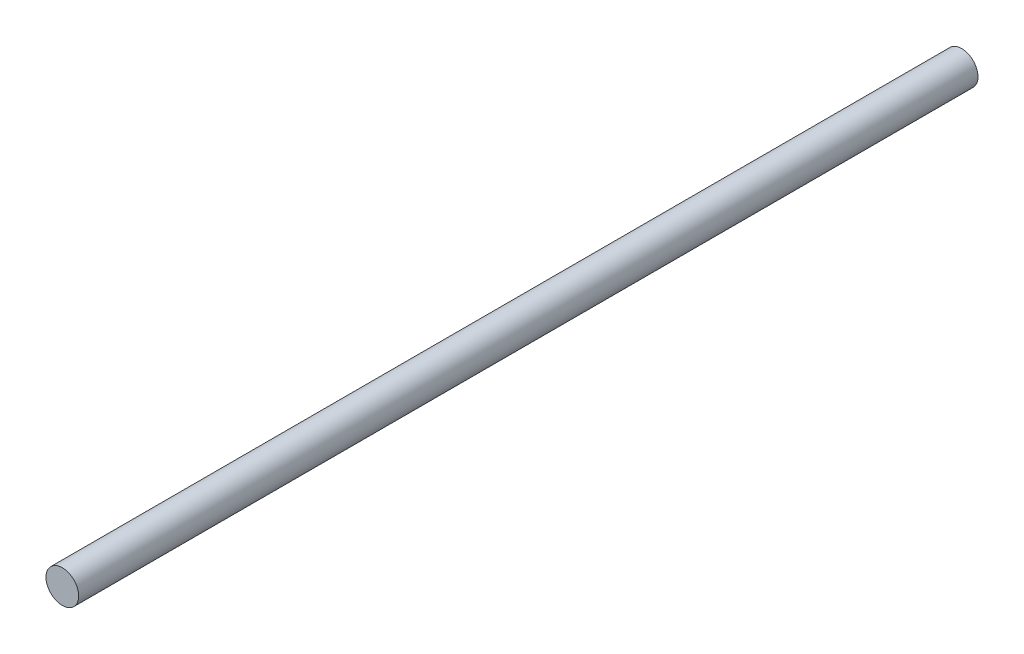
SolidWorks part; units mm, degrees
ref_plane "Plan de face" through (0, 0, 0) normal (0, 0, 1) x (1, 0, 0)
ref_plane "Plan de dessus" through (0, 0, 0) normal (0, 1, 0) x (1, 0, 0)
ref_plane "Plan de droite" through (0, 0, 0) normal (1, 0, 0) x (0, 0, -1)
sketch "Esquisse1" plane through (0, 0, 0) normal (0, 0, 1) x (1, 0, 0)
  circle A0 centre (0, 0) radius 4
extrude "Boss.-Extru.1" add sketch "Esquisse1" along normal blind 220
